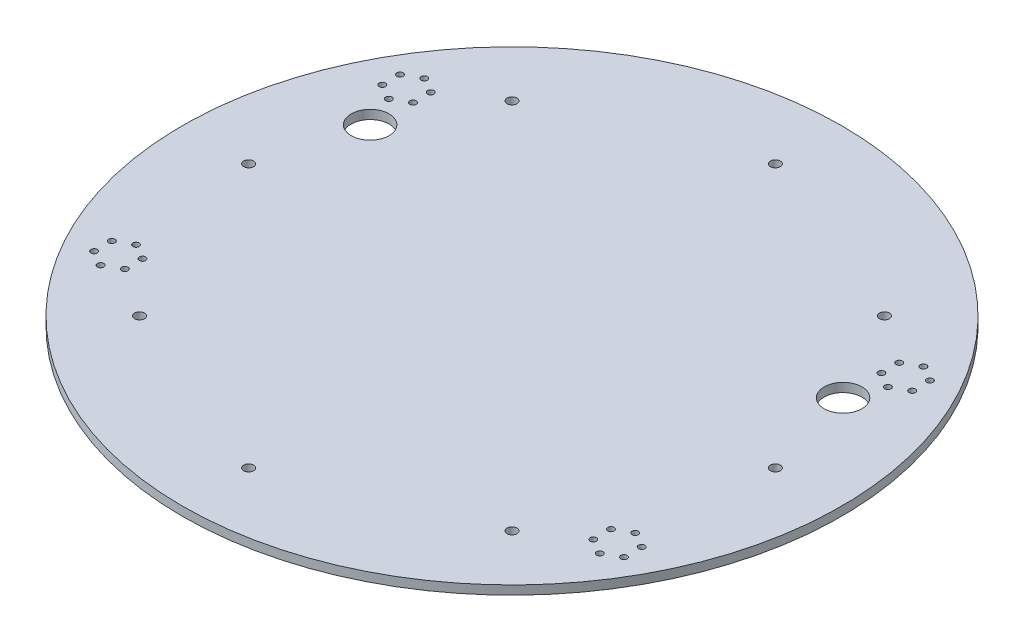
SolidWorks part; units mm, degrees
ref_plane "Front Plane" through (0, 0, 0) normal (0, 0, 1) x (1, 0, 0)
ref_plane "Top Plane" through (0, 0, 0) normal (0, 1, 0) x (1, 0, 0)
ref_plane "Right Plane" through (0, 0, 0) normal (1, 0, 0) x (0, 0, -1)
sketch "Sketch1" plane through (0, 0, 0) normal (0, 1, 0) x (1, 0, 0)
  circle A0 centre (0, 0) radius 177
  dimension "D1" = 354
extrude "Boss-Extrude1" add sketch "Sketch1" along normal blind 4.7625
sketch "Sketch2" plane through (0, 4.7625, 0) normal (0, 1, 0) x (1, 0, 0)
  line L0 (0, 177) -> (0, -177) construction
  line L1 (-177, 0) -> (177, 0) construction
  circle A47 centre (0, 0) radius 177 construction
  circle A48 centre (142.288, -82.15) radius 1.7
  circle A49 centre (134.0391, -86.9125) radius 1.7
  circle A50 centre (125.7902, -82.15) radius 1.7
  circle A51 centre (125.7902, -72.625) radius 1.7
  circle A52 centre (134.0391, -67.8625) radius 1.7
  circle A53 centre (142.288, -72.625) radius 1.7
  circle A54 centre (-142.288, -72.625) radius 1.7
  circle A55 centre (-134.0391, -67.8625) radius 1.7
  circle A56 centre (-125.7902, -72.625) radius 1.7
  circle A57 centre (-125.7902, -82.15) radius 1.7
  circle A58 centre (-134.0391, -86.9125) radius 1.7
  circle A59 centre (-142.288, -82.15) radius 1.7
  circle A60 centre (-142.288, 82.15) radius 1.7
  circle A61 centre (-134.0391, 86.9125) radius 1.7
  circle A62 centre (-125.7902, 82.15) radius 1.7
  circle A63 centre (-125.7902, 72.625) radius 1.7
  circle A64 centre (-134.0391, 67.8625) radius 1.7
  circle A65 centre (-142.288, 72.625) radius 1.7
  circle A66 centre (142.288, 72.625) radius 1.7
  circle A67 centre (134.0391, 67.8625) radius 1.7
  circle A68 centre (125.7902, 72.625) radius 1.7
  circle A69 centre (125.7902, 82.15) radius 1.7
  circle A70 centre (134.0391, 86.9125) radius 1.7
  circle A71 centre (142.288, 82.15) radius 1.7
  point P22 (134.0391, -77.3875)
  point P31 (-134.0391, -77.3875)
  point P56 (-134.0391, 77.3875)
  point P57 (134.0391, 77.3875)
  dimension "D2" = 3.4
  dimension "D5" = 6
extrude "Cut-Extrude1" cut sketch "Sketch2" against normal through all
sketch "Sketch3" plane through (0, 4.7625, 0) normal (0, 1, 0) x (1, 0, 0)
  line L0 (0, 177) -> (0, -177) construction
  circle A0 centre (0, -141.44) radius 2.667
  circle A1 centre (0, 0) radius 177 construction
  circle A2 centre (-100.0132, -100.0132) radius 2.667
  circle A3 centre (-141.44, 0) radius 2.667
  circle A4 centre (-100.0132, 100.0132) radius 2.667
  circle A5 centre (0, 141.44) radius 2.667
  circle A6 centre (100.0132, 100.0132) radius 2.667
  circle A7 centre (141.44, 0) radius 2.667
  circle A8 centre (100.0132, -100.0132) radius 2.667
  point P24 (0, 0)
  dimension "D1" = 5.334
  dimension "D2" = 35.56
  dimension "D3" = 8
extrude "Zip Ties" cut sketch "Sketch3" against normal through all
sketch "Sketch4" plane through (0, 4.7625, 0) normal (0, 1, 0) x (1, 0, 0)
  circle A0 centre (-127, 50.8) radius 10.16
  circle A1 centre (127, 50.8) radius 10.16
  point P5 (108.2639, 50.8)
  dimension "D1" = 20.32
  dimension "D3" = 50.8
  dimension "D2" = 127
  dimension "D4" = 127
  dimension "D5" = 50.8
extrude "Wires" cut sketch "Sketch4" against normal through all
